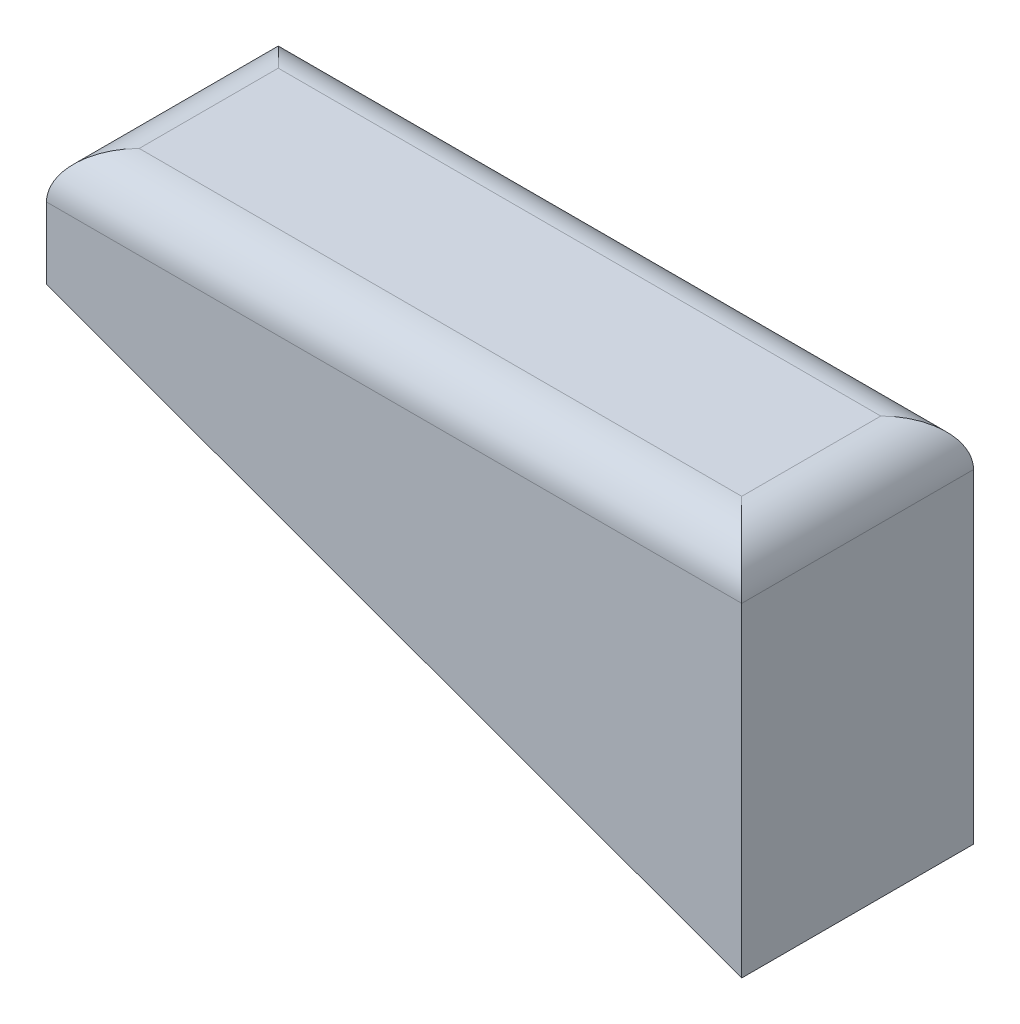
SolidWorks part; units mm, degrees
ref_plane "Alzado" through (0, 0, 0) normal (0, 0, 1) x (1, 0, 0)
ref_plane "Planta" through (0, 0, 0) normal (0, 1, 0) x (1, 0, 0)
ref_plane "Vista lateral" through (0, 0, 0) normal (1, 0, 0) x (0, 0, -1)
sketch "Croquis1" plane through (0, 0, 0) normal (0, 0, 1) x (1, 0, 0)
  line L0 (0, 0) -> (-15, 5.4596)
  line L1 (-15, 5.4596) -> (-15, 8)
  line L2 (-15, 8) -> (0, 8)
  line L3 (0, 8) -> (0, 0)
  line L4 (0, 0) -> (-0.199, -0.4478)
  line L5 (0, 0) -> (-21.2935, 0) construction
  dimension "D1" = 8
  dimension "D2" = 15
  dimension "D3" = 20
  dimension "D4" = 15.9627
extrude "Saliente-Extruir1" add sketch "Croquis1" along normal blind 5 contours L3 L2 L1 L0
fillet "Redondeo1" radius 1 4 edges at (-7.5, 8, 0) (-15, 8, 2.5) (-7.5, 8, 5) (0, 8, 2.5)
